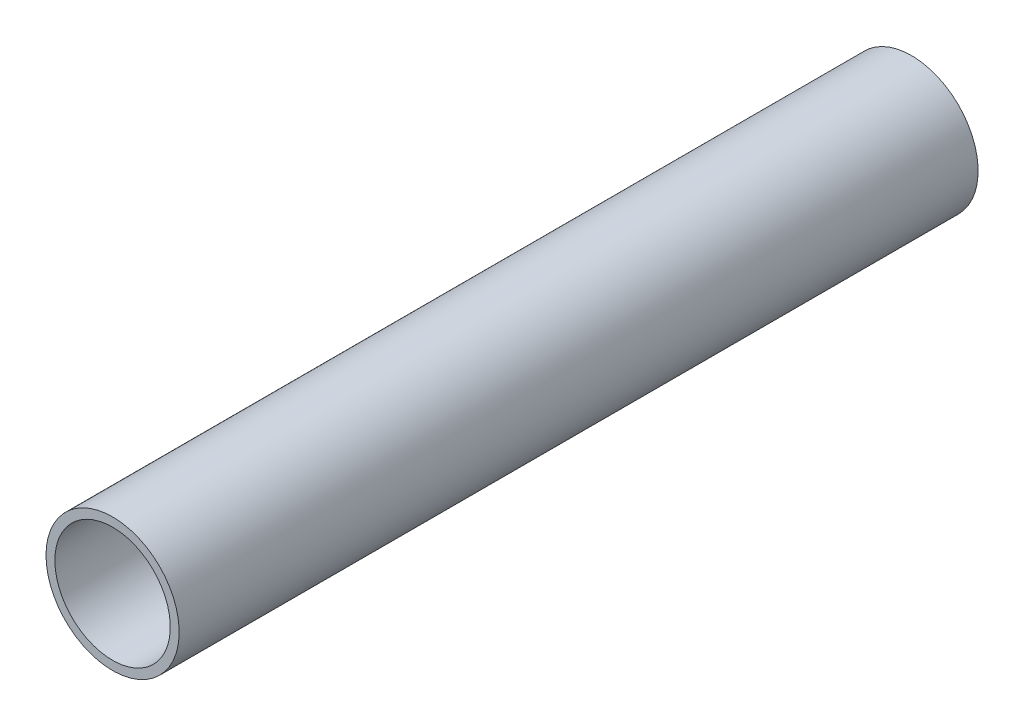
SolidWorks part; units mm, degrees
ref_plane "Front Plane" through (0, 0, 0) normal (0, 0, 1) x (1, 0, 0)
ref_plane "Top Plane" through (0, 0, 0) normal (0, 1, 0) x (1, 0, 0)
ref_plane "Right Plane" through (0, 0, 0) normal (1, 0, 0) x (0, 0, -1)
sketch "Sketch1" plane through (0, 0, 0) normal (0, 0, 1) x (1, 0, 0)
  circle A0 centre (0, 0) radius 7.5
  circle A1 centre (0, 0) radius 6.5
  dimension "D1" = 15
  dimension "D2" = 13
extrude "Boss-Extrude1" add sketch "Sketch1" along normal blind 90
